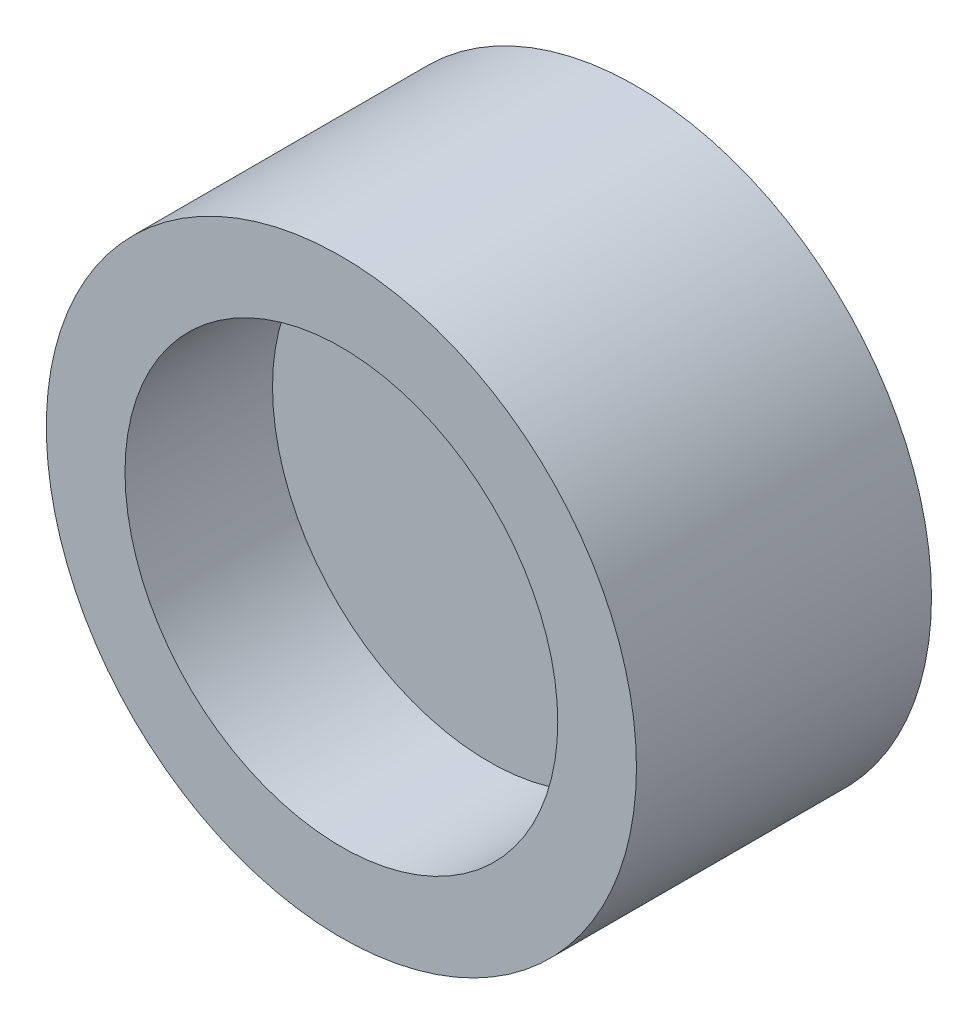
SolidWorks part; units mm, degrees
ref_plane "Front" through (0, 0, 0) normal (0, 0, 1) x (1, 0, 0)
ref_plane "Top" through (0, 0, 0) normal (0, 1, 0) x (1, 0, 0)
ref_plane "Right" through (0, 0, 0) normal (1, 0, 0) x (0, 0, -1)
sketch "Эскиз1" plane through (0, 0, 0) normal (0, 0, 1) x (1, 0, 0)
  circle A0 centre (0, 0) radius 3
extrude "Бобышка-Вытянуть1" add sketch "Эскиз1" along normal blind 3
sketch "Эскиз2" plane through (0, 0, 3) normal (0, 0, 1) x (1, 0, 0)
  circle A0 centre (0, 0) radius 2.2
extrude "Вырез-Вытянуть1" cut sketch "Эскиз2" against normal blind 1.5
